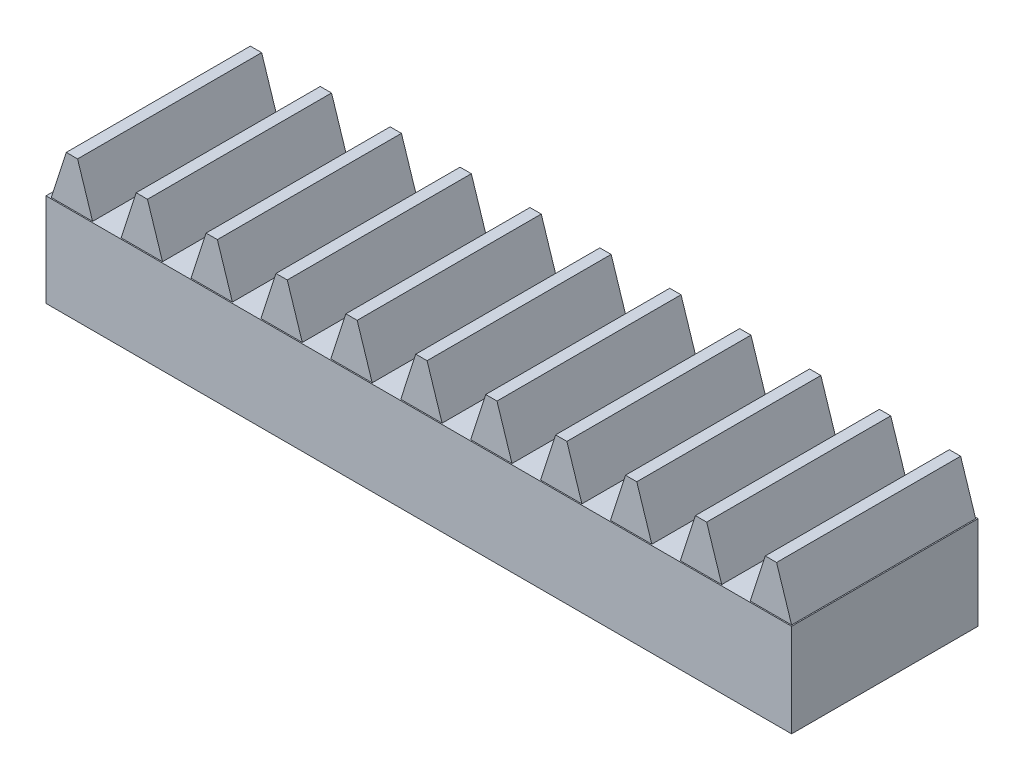
SolidWorks part; units mm, degrees
ref_plane "Front Plane" through (0, 0, 0) normal (0, 0, 1) x (1, 0, 0)
ref_plane "Top Plane" through (0, 0, 0) normal (0, 1, 0) x (1, 0, 0)
ref_plane "Right Plane" through (0, 0, 0) normal (1, 0, 0) x (0, 0, -1)
sketch "Sketch1" plane through (0, 0, 0) normal (0, 1, 0) x (1, 0, 0)
  line L7 (48.7742, -5.0968) -> (80.7742, -5.0968)
  line L8 (48.7742, -5.0968) -> (48.7742, -13.0968)
  line L9 (48.7742, -13.0968) -> (80.7742, -13.0968)
  line L10 (80.7742, -5.0968) -> (80.7742, -13.0968)
  dimension "D1" = 8
  dimension "D2" = 32
extrude "Boss-Extrude1" add sketch "Sketch1" along normal blind 4
sketch "Sketch2" plane through (0, 4, 0) normal (0, 1, 0) x (1, 0, 0)
  line L0 (48.7742, -5.0968) -> (48.7742, -13.0968) construction
  line L2 (80.7242, -13.0468) -> (48.8242, -13.0468)
  line L3 (80.7242, -13.0468) -> (80.7242, -5.1468)
  line L4 (80.7242, -5.1468) -> (48.8242, -5.1468)
  line L5 (80.7742, -13.0968) -> (80.7742, -5.0968) construction
  line L7 (48.7742, -13.0968) -> (80.7742, -13.0968) construction
  line L8 (80.7742, -5.0968) -> (48.7742, -5.0968) construction
  line L9 (48.8242, -13.0468) -> (48.8242, -5.1468)
  dimension "D2" = 0.05
  dimension "D1" = 0.05
  dimension "D3" = 0.05
  dimension "D4" = 0.05
extrude "Boss-Extrude2" add sketch "Sketch2" along normal blind 2
sketch "Sketch3" plane through (0, 0, 5.1468) normal (0, 0, -1) x (-1, 0, 0)
  line L0 (-80.7242, 6) -> (-80.7242, 4) construction
  line L1 (-77.7242, 4) -> (-77.0792, 6)
  line L2 (-79.5942, 6) -> (-77.0792, 6)
  line L3 (-82.5942, 6) -> (-81.9492, 4)
  line L4 (-81.9492, 4) -> (-80.7242, 4)
  line L5 (-80.7242, 4) -> (-80.0792, 6)
  line L6 (-82.5942, 6) -> (-80.0792, 6)
  line L7 (-80.7242, 4) -> (-48.8242, 4) construction
  line L8 (-80.7742, 4) -> (-48.7742, 4) construction
  line L9 (-78.9492, 4) -> (-77.7242, 4)
  line L10 (-79.5942, 6) -> (-78.9492, 4)
  line L11 (-74.7242, 4) -> (-74.0792, 6)
  line L12 (-76.5942, 6) -> (-74.0792, 6)
  line L13 (-75.9492, 4) -> (-74.7242, 4)
  line L14 (-76.5942, 6) -> (-75.9492, 4)
  line L15 (-71.7242, 4) -> (-71.0792, 6)
  line L16 (-73.5942, 6) -> (-71.0792, 6)
  line L17 (-72.9492, 4) -> (-71.7242, 4)
  line L18 (-73.5942, 6) -> (-72.9492, 4)
  line L19 (-68.7242, 4) -> (-68.0792, 6)
  line L20 (-70.5942, 6) -> (-68.0792, 6)
  line L21 (-69.9492, 4) -> (-68.7242, 4)
  line L22 (-70.5942, 6) -> (-69.9492, 4)
  line L23 (-65.7242, 4) -> (-65.0792, 6)
  line L24 (-67.5942, 6) -> (-65.0792, 6)
  line L25 (-66.9492, 4) -> (-65.7242, 4)
  line L26 (-67.5942, 6) -> (-66.9492, 4)
  line L27 (-62.7242, 4) -> (-62.0792, 6)
  line L28 (-64.5942, 6) -> (-62.0792, 6)
  line L29 (-63.9492, 4) -> (-62.7242, 4)
  line L30 (-64.5942, 6) -> (-63.9492, 4)
  line L31 (-59.7242, 4) -> (-59.0792, 6)
  line L32 (-61.5942, 6) -> (-59.0792, 6)
  line L33 (-60.9492, 4) -> (-59.7242, 4)
  line L34 (-61.5942, 6) -> (-60.9492, 4)
  line L35 (-56.7242, 4) -> (-56.0792, 6)
  line L36 (-58.5942, 6) -> (-56.0792, 6)
  line L37 (-57.9492, 4) -> (-56.7242, 4)
  line L38 (-58.5942, 6) -> (-57.9492, 4)
  line L39 (-53.7242, 4) -> (-53.0792, 6)
  line L40 (-55.5942, 6) -> (-53.0792, 6)
  line L41 (-54.9492, 4) -> (-53.7242, 4)
  line L42 (-55.5942, 6) -> (-54.9492, 4)
  line L43 (-50.7242, 4) -> (-50.0792, 6)
  line L44 (-52.5942, 6) -> (-50.0792, 6)
  line L45 (-51.9492, 4) -> (-50.7242, 4)
  line L46 (-52.5942, 6) -> (-51.9492, 4)
  line L47 (-80.7242, 4) -> (-77.7242, 4) construction
  line L48 (-47.7242, 4) -> (-47.0792, 6)
  line L49 (-49.5942, 6) -> (-47.0792, 6)
  line L50 (-48.9492, 4) -> (-47.7242, 4)
  line L51 (-49.5942, 6) -> (-48.9492, 4)
  line L52 (-44.7242, 4) -> (-44.0792, 6)
  line L53 (-46.5942, 6) -> (-44.0792, 6)
  line L54 (-45.9492, 4) -> (-44.7242, 4)
  line L55 (-46.5942, 6) -> (-45.9492, 4)
  dimension "D1" = 252.125
  dimension "D2" = 252.125
  dimension "D3" = 2
  dimension "D4" = 1.225
  dimension "D5" = 13
  dimension "D6" = 3
sketch "Sketch4" plane through (0, 0, 0) normal (0, -1, 0) x (1, 0, 0)
  line L0 (48.7742, 13.0968) -> (80.7742, 13.0968) construction
  line L1 (50.2742, 11.5968) -> (79.2742, 11.5968)
  line L2 (50.2742, 11.5968) -> (50.2742, 6.5968)
  line L3 (50.2742, 6.5968) -> (79.2742, 6.5968)
  line L4 (79.2742, 11.5968) -> (79.2742, 6.5968)
  line L5 (80.7742, 5.0968) -> (48.7742, 5.0968) construction
  line L6 (80.7742, 13.0968) -> (80.7742, 5.0968) construction
  line L7 (48.7742, 5.0968) -> (48.7742, 13.0968) construction
  dimension "D1" = 1.5
  dimension "D2" = 1.5
  dimension "D3" = 1.5
  dimension "D4" = 1.5
extrude "Cut-Extrude2" cut sketch "Sketch4" against normal blind 3
extrude "Cut-Extrude3" cut sketch "Sketch3" against normal blind 10
